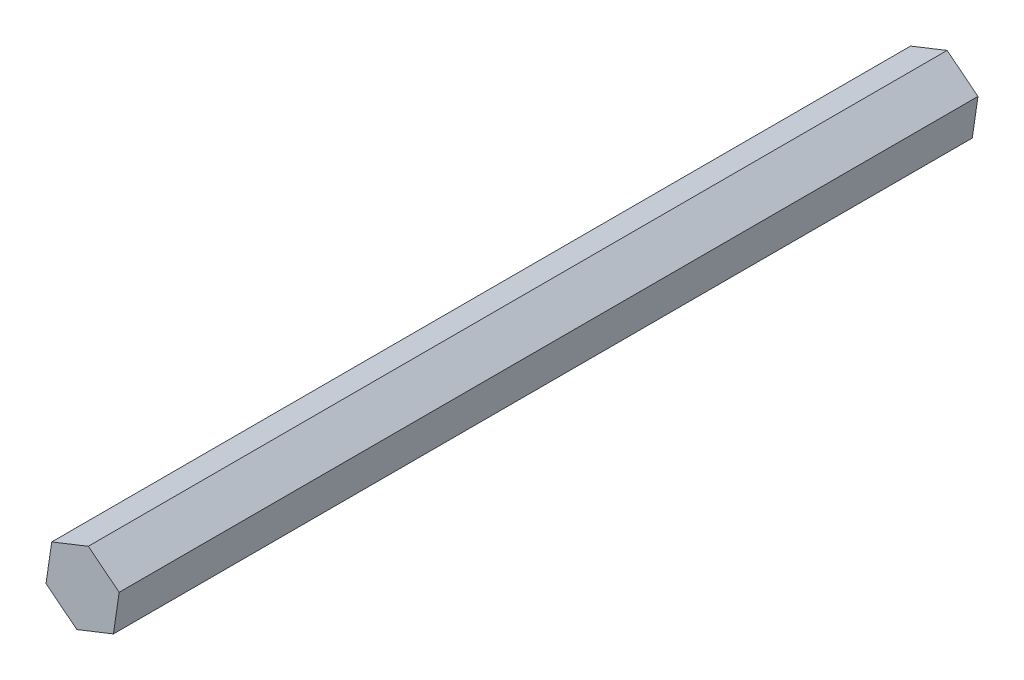
SolidWorks part; units mm, degrees
ref_plane "Front Plane" through (0, 0, 0) normal (0, 0, 1) x (1, 0, 0)
ref_plane "Top Plane" through (0, 0, 0) normal (0, 1, 0) x (1, 0, 0)
ref_plane "Right Plane" through (0, 0, 0) normal (1, 0, 0) x (0, 0, -1)
sketch "Sketch1" plane through (0, 0, 0) normal (0, 0, 1) x (1, 0, 0)
  line L1 (1.0649, 7.2546) -> (-5.7502, 4.5495)
  line L2 (-5.7502, 4.5495) -> (-6.8151, -2.7051)
  line L3 (-6.8151, -2.7051) -> (-1.0649, -7.2546)
  line L4 (-1.0649, -7.2546) -> (5.7502, -4.5495)
  line L5 (5.7502, -4.5495) -> (6.8151, 2.7051)
  line L6 (6.8151, 2.7051) -> (1.0649, 7.2546)
  circle A0 centre (0, 0) radius 6.35 construction
  dimension "D1" = 12.7
extrude "Boss-Extrude1" add sketch "Sketch1" along normal blind 160.02
